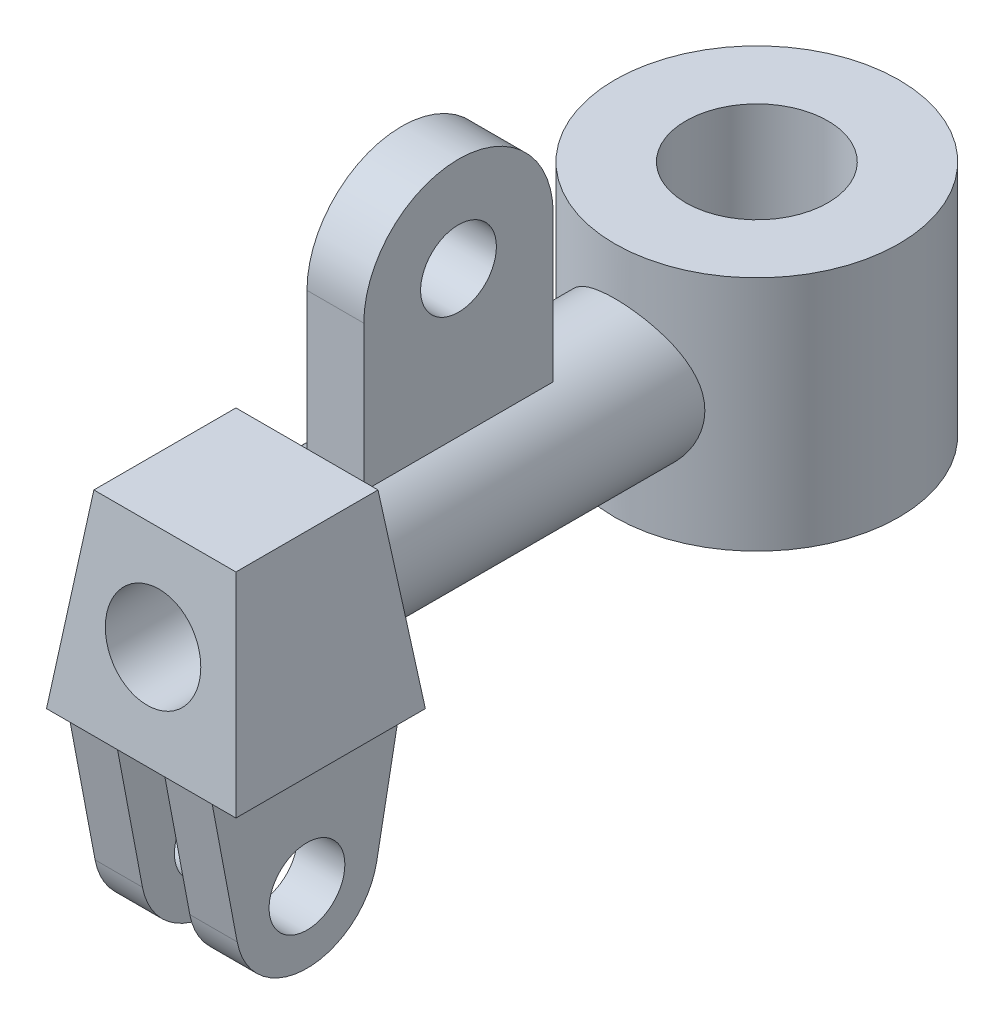
SolidWorks part; units mm, degrees
ref_plane "Front Plane" through (0, 0, 0) normal (0, 0, 1) x (1, 0, 0)
ref_plane "Top Plane" through (0, 0, 0) normal (0, 1, 0) x (1, 0, 0)
ref_plane "Right Plane" through (0, 0, 0) normal (1, 0, 0) x (0, 0, -1)
sketch "Sketch1" plane through (0, 0, 0) normal (0, 1, 0) x (1, 0, 0)
  line L1 (-20, 20) -> (20, 20)
  line L2 (-20, 20) -> (-20, -20)
  line L3 (-20, -20) -> (20, -20)
  line L4 (20, 20) -> (20, -20)
  line L5 (-20, 20) -> (20, -20) construction
  line L6 (-20, -20) -> (20, 20) construction
  point P0 (0, 0)
  dimension "D1" = 40
  dimension "D2" = 40
extrude "Boss-Extrude1" add sketch "Sketch1" along normal blind 40 draft 7.125
ref_plane "Plane1" through (0, 20, 0) normal (0, 1, 0) x (1, 0, 0)
sketch "Sketch2" plane through (0, 20, 0) normal (0, 1, 0) x (1, 0, 0)
  circle A0 centre (0, 110) radius 30
  point P2 (0, 0)
  dimension "D1" = 60
  dimension "D2" = 110
extrude "Boss-Extrude2" add sketch "Sketch2" along normal mid plane 50 separate body
sketch "Sketch3" plane through (0, 0, 0) normal (0, 0, 1) x (1, 0, 0)
  circle A0 centre (0, 20) radius 15
  point P2 (0, 0)
  dimension "D1" = 30
  dimension "D2" = 20
extrude "Boss-Extrude3" add sketch "Sketch3" against normal up to surface (84.0192 mm away)
sketch "Sketch4" plane through (0, 0, 0) normal (1, 0, 0) x (0, 0, -1)
  line L0 (20, 64) -> (20, 20)
  line L1 (20, 20) -> (60, 20)
  line L2 (60, 20) -> (60, 64)
  line L3 (-17.5, 20) -> (158.8013, 20) construction
  line L4 (-15, 40) -> (-20, 0) construction
  arc A0 (60, 64) -> (20, 64) centre (40, 64) ccw
  circle A1 centre (40, 64) radius 8
  dimension "D2" = 40
  dimension "D5" = 16
  dimension "D1" = 40
  dimension "D3" = 44
  dimension "D4" = 20
extrude "Boss-Extrude4" add sketch "Sketch4" along normal blind 12 from offset 5 offset against normal yes
sketch "Sketch5" plane through (0, 0, 0) normal (1, 0, 0) x (0, 0, -1)
  line L0 (-20, 0) -> (20, 0)
  line L1 (20, 0) -> (14.7381, -27.7905)
  line L2 (-20, 0) -> (-14.7381, -27.7905)
  arc A0 (-14.7381, -27.7905) -> (14.7381, -27.7905) centre (0, -25) ccw
  circle A1 centre (0, -25) radius 8
  dimension "D1" = 30
  dimension "D3" = 16
  dimension "D2" = 25
extrude "Boss-Extrude5" add sketch "Sketch5" along normal blind 10 from offset 5
mirror "Mirror1" about plane through (0, 0, 0) normal (1, 0, 0) of "Boss-Extrude5"
sketch "Sketch8" plane through (0, 0, 0) normal (0, 0, 1) x (1, 0, 0)
  line L0 (-30, -5) -> (30, -5) construction
  circle A0 centre (0, 20) radius 10
  dimension "D1" = 20
  dimension "D2" = 25
extrude "Cut-Extrude1" cut sketch "Sketch8" along normal up to surface and the other way blind 100 up to face at (0, 10, 18.75)
hole_wizard "Hole1" positions "Sketch9" profile "Sketch10" legacy end condition through all
sketch "Sketch9" plane through (0, 45, 0) normal (0, 1, 0) x (1, 0, 0)
  point P0 (0, 110)
sketch "Sketch10" plane through (0, 45, -110) normal (1, 0, 0) x (0, 0, 1)
  line L0 (0, 0) -> (0, 85)
  line L1 (0, 85) -> (15, 85)
  line L2 (15, 85) -> (15, 0)
  line L3 (15, 0) -> (0, 0)
  line L4 (0, 110) -> (0, -10) construction
  dimension "Diameter" = 30
  dimension "Depth" = 85
